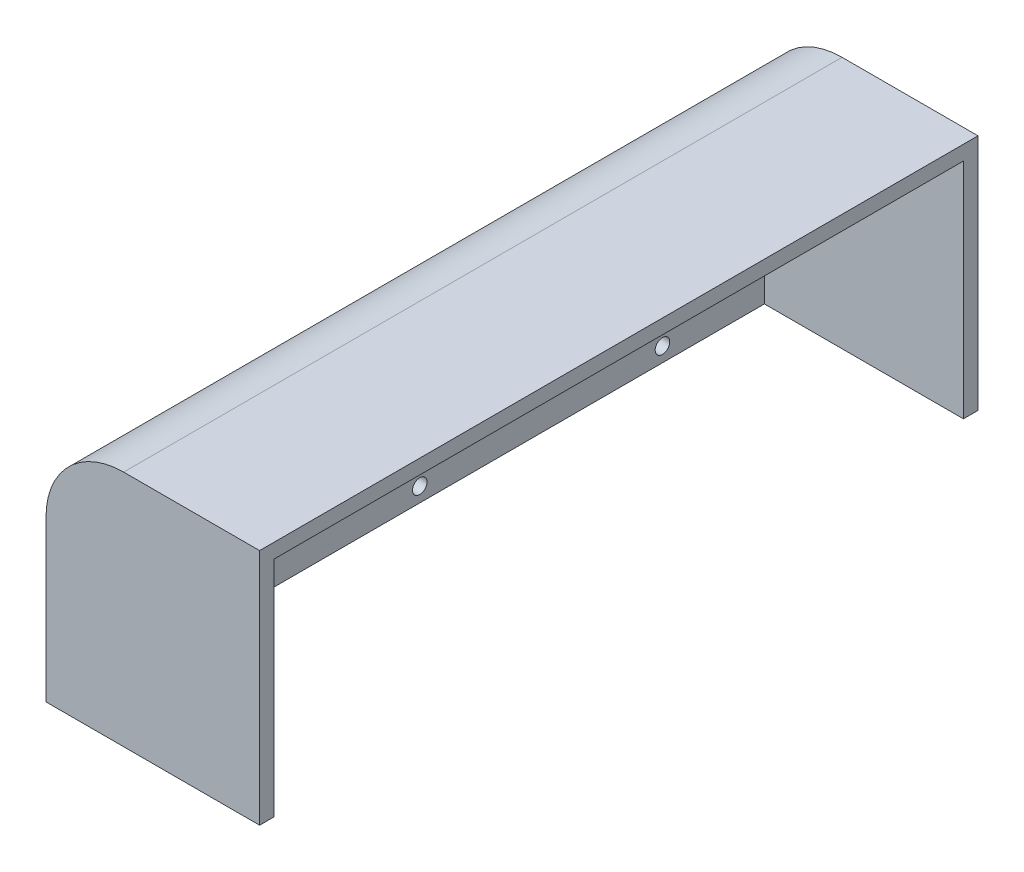
SolidWorks part; units mm, degrees
ref_plane "Front Plane" through (0, 0, 0) normal (0, 0, 1) x (1, 0, 0)
ref_plane "Top Plane" through (0, 0, 0) normal (0, 1, 0) x (1, 0, 0)
ref_plane "Right Plane" through (0, 0, 0) normal (1, 0, 0) x (0, 0, -1)
sketch "Sketch2" plane through (0, 0, 0) normal (0, 1, 0) x (1, 0, 0)
  line L0 (-10.5, -35.5) -> (10, -35.5)
  line L1 (-10, 35) -> (10, 35) construction
  line L2 (-10, 35) -> (-10, -35) construction
  line L3 (-10, -35) -> (10, -35) construction
  line L4 (10, 35) -> (10, -35) construction
  line L5 (-10, 35) -> (10, -35) construction
  line L6 (-10, -35) -> (10, 35) construction
  line L7 (-10.5, 35.5) -> (-10.5, -35.5)
  line L8 (-10.5, 35.5) -> (10, 35.5)
  line L9 (-12, -37) -> (10, -37)
  line L10 (-12, 37) -> (-12, -37)
  line L11 (-12, 37) -> (10, 37)
  line L12 (10, 37) -> (10, 35.5)
  line L13 (10, -35.5) -> (10, -37)
  point P0 (0, 0)
  dimension "D1" = 20
  dimension "D2" = 70
  dimension "D3" = 0.5
  dimension "D4" = 1.5
extrude "Boss-Extrude1" add sketch "Sketch2" along normal blind 23
sketch "Sketch3" plane through (0, 23, 0) normal (0, 1, 0) x (1, 0, 0)
  line L1 (-12, 37) -> (10, 37)
  line L2 (-12, 37) -> (-12, -37)
  line L3 (-12, -37) -> (10, -37)
  line L4 (10, 37) -> (10, -37)
extrude "Boss-Extrude2" add sketch "Sketch3" along normal blind 1.5
fillet "Fillet1" radius 8 2 edges at (-10.5, 23, 0) (-12, 24.5, 0)
sketch "Sketch4" plane through (-12, 0, 0) normal (-1, 0, 0) x (0, 0, 1)
  circle A0 centre (-25, 1.5) radius 0.75
  circle A1 centre (0, 1.5) radius 0.75
  circle A2 centre (25, 1.5) radius 0.75
extrude "Cut-Extrude1" cut sketch "Sketch4" against normal through all both and the other way through all
